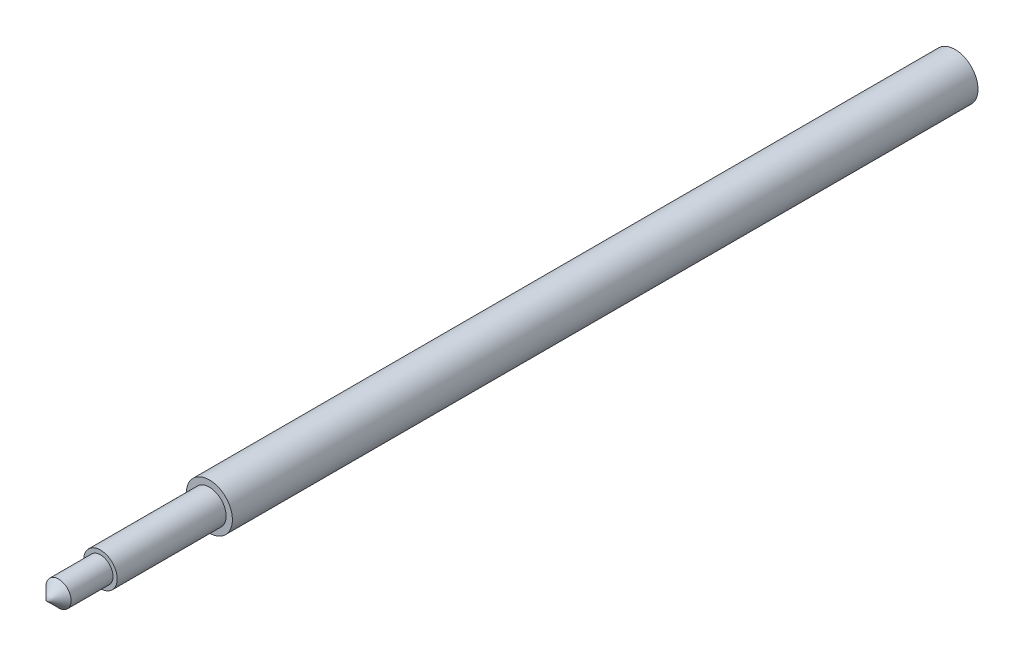
SolidWorks part; units mm, degrees
ref_plane "前视基准面" through (0, 0, 0) normal (0, 0, 1) x (1, 0, 0)
ref_plane "上视基准面" through (0, 0, 0) normal (0, 1, 0) x (1, 0, 0)
ref_plane "右视基准面" through (0, 0, 0) normal (1, 0, 0) x (0, 0, -1)
sketch "草图1" plane through (0, 0, 0) normal (0, 0, 1) x (1, 0, 0)
  line L0 (0, 0) -> (9.0589, 0) construction
  line L1 (0, 0) -> (0, 6.7556) construction
  circle A0 centre (0, 0) radius 2.75
  dimension "D1" = 5.5
extrude "凸台-拉伸1" add sketch "草图1" along normal blind 89
sketch "草图2" plane through (0, 0, 89) normal (0, 0, 1) x (1, 0, 0)
  circle A0 centre (0, 0) radius 2
  dimension "D1" = 4
extrude "凸台-拉伸2" add sketch "草图2" along normal blind 13
sketch "草图3" plane through (0, 0, 102) normal (0, 0, 1) x (1, 0, 0)
  circle A2 centre (0, 0) radius 1.5
  circle A3 centre (0, 0) radius 1.5
  dimension "D1" = 0.5
extrude "凸台-拉伸3" add sketch "草图3" along normal blind 5
sketch "草图4" plane through (0, 0, 0) normal (0, 1, 0) x (1, 0, 0)
  line L0 (0, -107) -> (0, -111.4342) construction
  line L2 (0, -107) -> (4.2373, -107) construction
  line L3 (0, -107) -> (0, -108.5)
  line L4 (0, -108.5) -> (-1.5, -107)
  line L5 (-1.5, -107) -> (1.5, -107) construction
  line L7 (-1.5, -107) -> (0, -107)
  dimension "D1" = 45.001
  dimension "D2" = 3
revolve "旋转1" add sketch "草图4" angle 360 about L0
